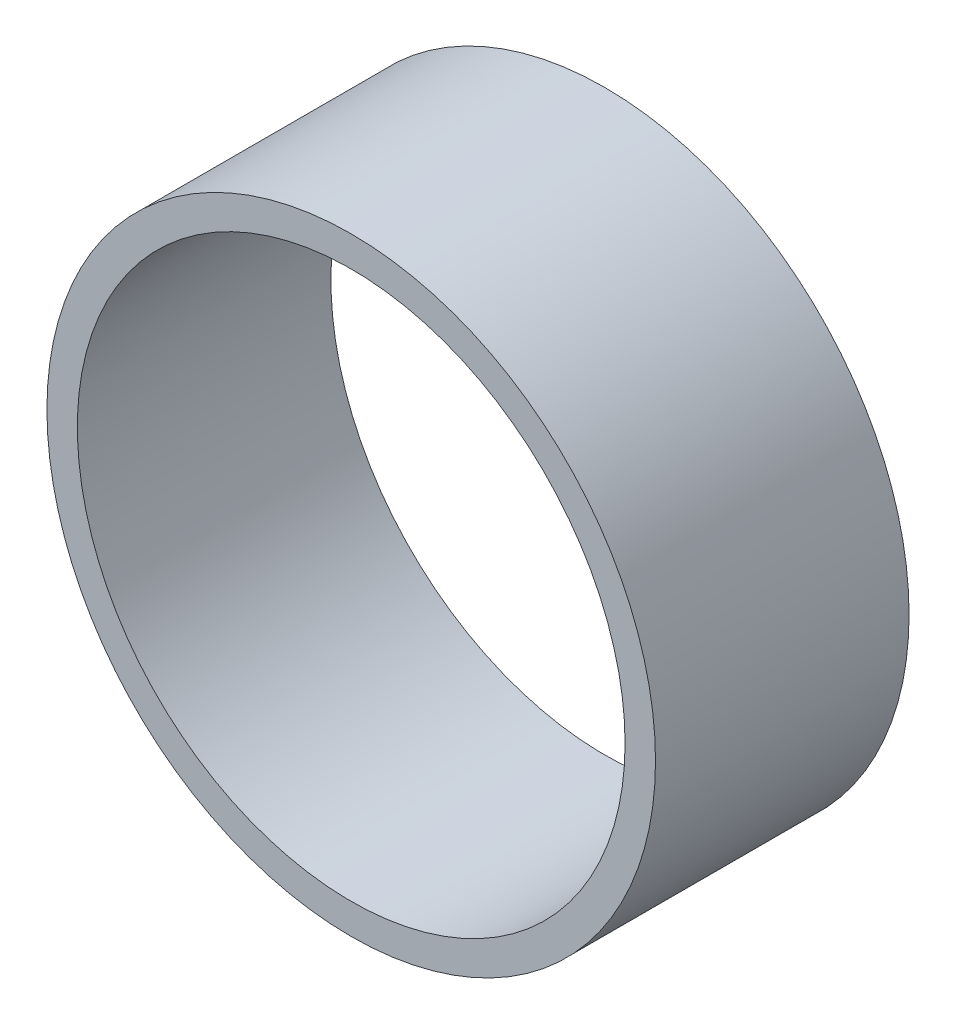
SolidWorks part; units mm, degrees
ref_plane "Front" through (0, 0, 0) normal (0, 0, 1) x (1, 0, 0)
ref_plane "Top" through (0, 0, 0) normal (0, 1, 0) x (1, 0, 0)
ref_plane "Right" through (0, 0, 0) normal (1, 0, 0) x (0, 0, -1)
sketch "Esquisse1" plane through (0, 0, 0) normal (0, 0, 1) x (1, 0, 0)
  circle A0 centre (0, 0) radius 27
  circle A1 centre (0, 0) radius 30
  dimension "D1" = 54
  dimension "D2" = 60
extrude "Boss.-Extru.1" add sketch "Esquisse1" along normal blind 25
